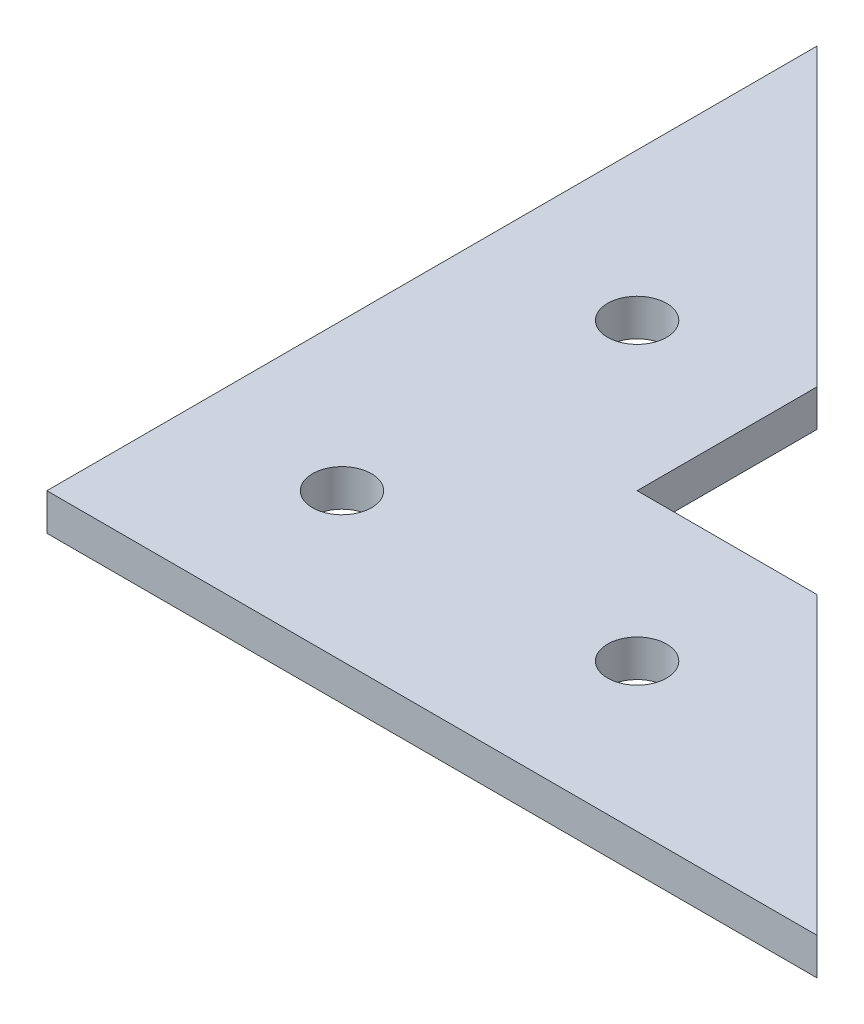
SolidWorks part; units mm, degrees
ref_plane "Front Plane" through (0, 0, 0) normal (0, 0, 1) x (1, 0, 0)
ref_plane "Top Plane" through (0, 0, 0) normal (0, 1, 0) x (1, 0, 0)
ref_plane "Right Plane" through (0, 0, 0) normal (1, 0, 0) x (0, 0, -1)
sketch "Sketch2" plane through (0, 0, 0) normal (0, 1, 0) x (1, 0, 0)
  line L0 (52.6994, -13.6436) -> (78.0994, -39.0436)
  line L1 (78.0994, -39.0436) -> (78.0994, -54.5376)
  line L2 (78.0994, -54.5376) -> (93.5934, -54.5376)
  line L3 (93.5934, -54.5376) -> (118.9934, -79.9376)
  line L4 (118.9934, -79.9376) -> (52.6994, -79.9376)
  line L5 (52.6994, -79.9376) -> (52.6994, -13.6436)
  line L6 (52.6994, -13.6436) -> (118.9934, -13.6436) construction
  line L7 (118.9934, -13.6436) -> (118.9934, -79.9376) construction
  line L8 (118.9934, -79.9376) -> (52.6994, -13.6436) construction
  circle A0 centre (65.3994, -67.2376) radius 2.54
  circle A1 centre (90.7994, -67.2376) radius 2.54
  circle A2 centre (65.3994, -41.8376) radius 2.54
  dimension "D9" = 5.08
  dimension "D10" = 5.08
  dimension "D12" = 5.08
  dimension "D1" = 135
  dimension "D2" = 45
  dimension "D3" = 135
  dimension "D4" = 45
  dimension "D5" = 66.294
  dimension "D6" = 25.4
  dimension "D7" = 25.4
  dimension "D8" = 66.294
  dimension "D11" = 25.4
  dimension "D13" = 25.4
extrude "Boss-Extrude1" add sketch "Sketch2" along normal blind 3.175
